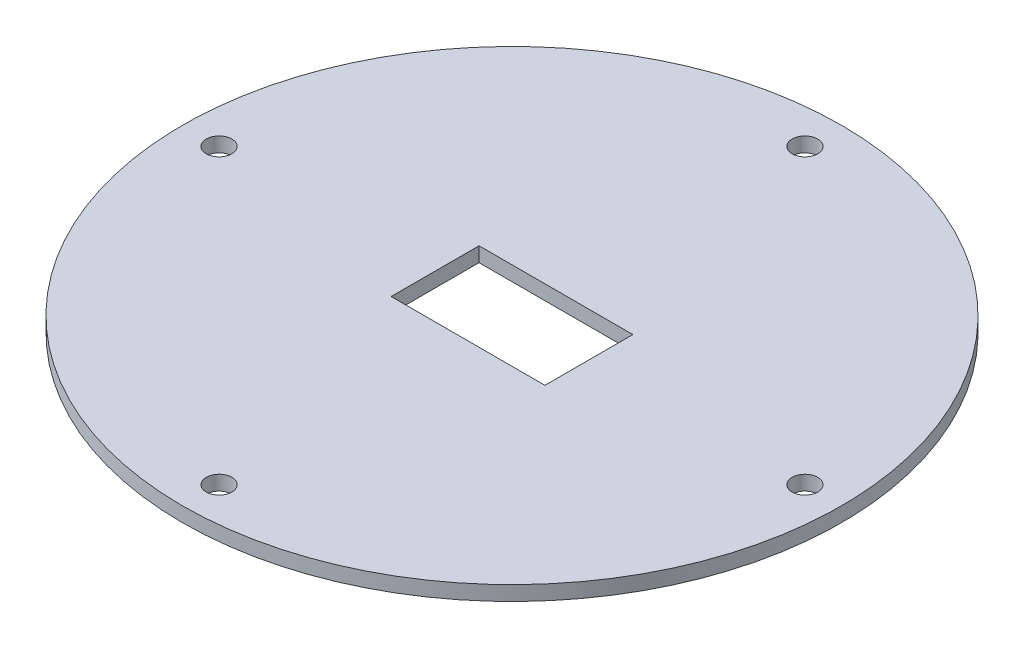
SolidWorks part; units mm, degrees
ref_plane "Front Plane" through (0, 0, 0) normal (0, 0, 1) x (1, 0, 0)
ref_plane "Top Plane" through (0, 0, 0) normal (0, 1, 0) x (1, 0, 0)
ref_plane "Right Plane" through (0, 0, 0) normal (1, 0, 0) x (0, 0, -1)
sketch "Sketch1" plane through (0, 0, 0) normal (0, 1, 0) x (1, 0, 0)
  circle A0 centre (0, 0) radius 45
  dimension "D1" = 90
extrude "Boss-Extrude1" add sketch "Sketch1" along normal blind 2
sketch "Sketch3" plane through (0, 2, 0) normal (0, 1, 0) x (1, 0, 0)
  circle A0 centre (0, 40) radius 1.75
  circle A1 centre (40, 0) radius 1.75
  circle A2 centre (0, -40) radius 1.75
  circle A3 centre (-40, 0) radius 1.75
  dimension "D2" = 3.5
  dimension "D1" = 40
  dimension "D3" = 4
extrude "Cut-Extrude1" cut sketch "Sketch3" against normal through all
sketch "Sketch4" plane through (0, 2, 0) normal (0, 1, 0) x (1, 0, 0)
  line L1 (-10.5, -6) -> (10.5, -6)
  line L2 (-10.5, -6) -> (-10.5, 6)
  line L3 (-10.5, 6) -> (10.5, 6)
  line L4 (10.5, -6) -> (10.5, 6)
  line L5 (-10.5, -6) -> (10.5, 6) construction
  line L6 (-10.5, 6) -> (10.5, -6) construction
  point P0 (0, 0)
  dimension "D1" = 12
  dimension "D2" = 21
extrude "Cut-Extrude2" cut sketch "Sketch4" against normal through all
